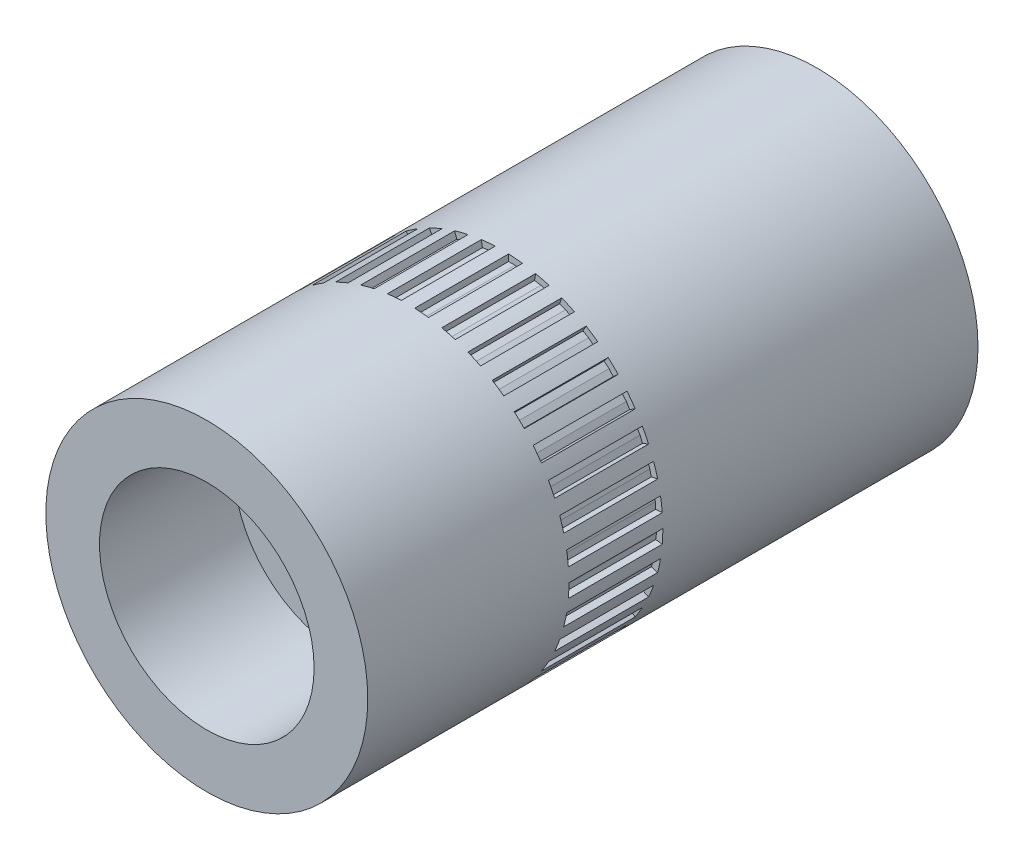
SolidWorks part; units mm, degrees
ref_plane "Ön Düzlem" through (0, 0, 0) normal (0, 0, 1) x (1, 0, 0)
ref_plane "Üst Düzlem" through (0, 0, 0) normal (0, 1, 0) x (1, 0, 0)
ref_plane "Sağ Düzlem" through (0, 0, 0) normal (1, 0, 0) x (0, 0, -1)
sketch "Çizim1" plane through (0, 0, 0) normal (0, 0, 1) x (1, 0, 0)
  circle A0 centre (0, 0) radius 9.1
  circle A1 centre (0, 0) radius 11
  circle A2 centre (0, 0) radius 12.559
  dimension "D1" = 18.2
  dimension "D2" = 22
extrude "Yükseklik-Ekstrüzyon1" add sketch "Çizim1" along normal blind 26.5 contours A1 A0
sketch "Çizim2" plane through (0, 0, 26.5) normal (0, 0, 1) x (1, 0, 0)
  circle A0 centre (0, 0) radius 12
  circle A1 centre (0, 0) radius 11
  circle A2 centre (0, 0) radius 11
  dimension "D2" = 24
  dimension "D1" = 0
extrude "Yükseklik-Ekstrüzyon2" add sketch "Çizim2" against normal blind 30.5
sketch "Çizim3" plane through (0, 0, 26.5) normal (0, 0, 1) x (1, 0, 0)
  line L0 (0, 12) -> (0, 11.629)
  line L1 (-0.5002, 12) -> (0.5002, 12)
  line L2 (0.5002, 12) -> (0.5002, 11.5)
  line L3 (-0.5002, 12) -> (-0.5002, 11.5)
  line L4 (0.5002, 11.5) -> (1.0002, 11.5)
  line L5 (-0.5002, 11.5) -> (-1.0002, 11.5)
  line L6 (1.4505, 11.4191) -> (0.9577, 11.5036)
  line L7 (1.535, 11.9119) -> (1.4505, 11.4191)
  line L8 (2.4365, 11.2501) -> (2.9293, 11.1656)
  line L9 (2.521, 11.7429) -> (2.4365, 11.2501)
  line L10 (1.535, 11.9119) -> (2.521, 11.7429)
  line L11 (3.3595, 11.0097) -> (2.8881, 11.1763)
  line L12 (3.5261, 11.4812) -> (3.3595, 11.0097)
  line L13 (4.3027, 10.6765) -> (4.7741, 10.5099)
  line L14 (4.4693, 11.1479) -> (4.3027, 10.6765)
  line L15 (3.5261, 11.4812) -> (4.4693, 11.1479)
  line L16 (5.1718, 10.2836) -> (4.7353, 10.5274)
  line L17 (5.4157, 10.7201) -> (5.1718, 10.2836)
  line L18 (6.0451, 9.7957) -> (6.4816, 9.5519)
  line L19 (6.289, 10.2322) -> (6.0451, 9.7957)
  line L20 (5.4157, 10.7201) -> (6.289, 10.2322)
  line L21 (6.8354, 9.2616) -> (6.4464, 9.5757)
  line L22 (7.1495, 9.6506) -> (6.8354, 9.2616)
  line L23 (7.6137, 8.6332) -> (8.0027, 8.3191)
  line L24 (7.9278, 9.0222) -> (7.6137, 8.6332)
  line L25 (7.1495, 9.6506) -> (7.9278, 9.0222)
  line L26 (8.3023, 7.9732) -> (7.972, 8.3486)
  line L27 (8.6776, 8.3036) -> (8.3023, 7.9732)
  line L28 (8.9632, 7.2223) -> (9.2935, 6.847)
  line L29 (9.3385, 7.5526) -> (8.9632, 7.2223)
  line L30 (8.6776, 8.3036) -> (9.3385, 7.5526)
  line L31 (9.5303, 6.4554) -> (9.2682, 6.8812)
  line L32 (9.9561, 6.7176) -> (9.5303, 6.4554)
  line L33 (10.0548, 5.6036) -> (10.317, 5.1779)
  line L34 (10.4806, 5.8658) -> (10.0548, 5.6036)
  line L35 (9.9561, 6.7176) -> (10.4806, 5.8658)
  line L36 (10.4842, 4.7519) -> (10.2978, 5.2159)
  line L37 (10.9482, 4.9384) -> (10.4842, 4.7519)
  line L38 (10.8572, 3.8238) -> (11.0436, 3.3598)
  line L39 (11.3212, 4.0102) -> (10.8572, 3.8238)
  line L40 (10.9482, 4.9384) -> (11.3212, 4.0102)
  line L41 (11.1365, 2.9117) -> (11.0312, 3.4005)
  line L42 (11.6253, 3.0171) -> (11.1365, 2.9117)
  line L43 (11.3473, 1.9339) -> (11.4526, 1.4451)
  line L44 (11.836, 2.0392) -> (11.3473, 1.9339)
  line L45 (11.6253, 3.0171) -> (11.836, 2.0392)
  line L46 (11.4684, 0.9878) -> (11.4472, 1.4873)
  line L47 (11.968, 1.009) -> (11.4684, 0.9878)
  line L48 (11.5109, -0.0116) -> (11.5321, -0.5112)
  line L49 (12.0104, 0.0096) -> (11.5109, -0.0116)
  line L50 (11.968, 1.009) -> (12.0104, 0.0096)
  line L51 (11.4704, -0.9646) -> (11.5339, -0.4686)
  line L52 (11.9663, -1.0281) -> (11.4704, -0.9646)
  line L53 (11.3433, -1.9568) -> (11.2798, -2.4528)
  line L54 (11.8393, -2.0203) -> (11.3433, -1.9568)
  line L55 (11.9663, -1.0281) -> (11.8393, -2.0203)
  line L56 (11.1424, -2.8892) -> (11.2888, -2.4111)
  line L57 (11.6205, -3.0356) -> (11.1424, -2.8892)
  line L58 (10.8495, -3.8457) -> (10.703, -4.3238)
  line L59 (11.3275, -3.9921) -> (10.8495, -3.8457)
  line L60 (11.6205, -3.0356) -> (11.3275, -3.9921)
  line L61 (10.4938, -4.7307) -> (10.7189, -4.2843)
  line L62 (10.9403, -4.9558) -> (10.4938, -4.7307)
  line L63 (10.0435, -5.6239) -> (9.8184, -6.0704)
  line L64 (10.4899, -5.8491) -> (10.0435, -5.6239)
  line L65 (10.9403, -4.9558) -> (10.4899, -5.8491)
  line L66 (9.5434, -6.4362) -> (9.8407, -6.0342)
  line L67 (9.9454, -6.7335) -> (9.5434, -6.4362)
  line L68 (8.9486, -7.2404) -> (8.6512, -7.6424)
  line L69 (9.3506, -7.5377) -> (8.9486, -7.2404)
  line L70 (9.9454, -6.7335) -> (9.3506, -7.5377)
  line L71 (8.3184, -7.9564) -> (8.6794, -7.6104)
  line L72 (8.6644, -8.3174) -> (8.3184, -7.9564)
  line L73 (7.5962, -8.6486) -> (7.2352, -8.9945)
  line L74 (7.9422, -9.0096) -> (7.5962, -8.6486)
  line L75 (8.6644, -8.3174) -> (7.9422, -9.0096)
  line L76 (6.8541, -9.2478) -> (7.2684, -8.9678)
  line L77 (7.1341, -9.662) -> (6.8541, -9.2478)
  line L78 (6.0253, -9.8079) -> (5.6111, -10.0879)
  line L79 (6.3053, -10.2222) -> (6.0253, -9.8079)
  line L80 (7.1341, -9.662) -> (6.3053, -10.2222)
  line L81 (5.1926, -10.2731) -> (5.6482, -10.0672)
  line L82 (5.3986, -10.7287) -> (5.1926, -10.2731)
  line L83 (4.2811, -10.6851) -> (3.8255, -10.8911)
  line L84 (4.4871, -11.1408) -> (4.2811, -10.6851)
  line L85 (5.3986, -10.7287) -> (4.4871, -11.1408)
  line L86 (3.3818, -11.0029) -> (3.8656, -10.8769)
  line L87 (3.5078, -11.4868) -> (3.3818, -11.0029)
  line L88 (2.4137, -11.255) -> (1.9299, -11.3809)
  line L89 (2.5397, -11.7388) -> (2.4137, -11.255)
  line L90 (3.5078, -11.4868) -> (2.5397, -11.7388)
  line L91 (1.4736, -11.4162) -> (1.9718, -11.3738)
  line L92 (1.516, -11.9144) -> (1.4736, -11.4162)
  line L93 (0.4769, -11.501) -> (-0.0213, -11.5434)
  line L94 (0.5193, -11.9992) -> (0.4769, -11.501)
  line L95 (1.516, -11.9144) -> (0.5193, -11.9992)
  line L96 (-0.4769, -11.501) -> (0.0213, -11.5434)
  line L97 (-0.5193, -11.9992) -> (-0.4769, -11.501)
  line L98 (-1.4736, -11.4162) -> (-1.9718, -11.3738)
  line L99 (-1.516, -11.9144) -> (-1.4736, -11.4162)
  line L100 (-0.5193, -11.9992) -> (-1.516, -11.9144)
  line L101 (-2.4137, -11.255) -> (-1.9299, -11.3809)
  line L102 (-2.5397, -11.7388) -> (-2.4137, -11.255)
  line L103 (-3.3818, -11.0029) -> (-3.8656, -10.8769)
  line L104 (-3.5078, -11.4868) -> (-3.3818, -11.0029)
  line L105 (-2.5397, -11.7388) -> (-3.5078, -11.4868)
  line L106 (-4.2811, -10.6851) -> (-3.8255, -10.8911)
  line L107 (-4.4871, -11.1408) -> (-4.2811, -10.6851)
  line L108 (-5.1926, -10.2731) -> (-5.6482, -10.0672)
  line L109 (-5.3986, -10.7287) -> (-5.1926, -10.2731)
  line L110 (-4.4871, -11.1408) -> (-5.3986, -10.7287)
  line L111 (-6.0253, -9.8079) -> (-5.6111, -10.0879)
  line L112 (-6.3053, -10.2222) -> (-6.0253, -9.8079)
  line L113 (-6.8541, -9.2478) -> (-7.2684, -8.9678)
  line L114 (-7.1341, -9.662) -> (-6.8541, -9.2478)
  line L115 (-6.3053, -10.2222) -> (-7.1341, -9.662)
  line L116 (-7.5962, -8.6486) -> (-7.2352, -8.9945)
  line L117 (-7.9422, -9.0096) -> (-7.5962, -8.6486)
  line L118 (-8.3184, -7.9564) -> (-8.6794, -7.6104)
  line L119 (-8.6644, -8.3174) -> (-8.3184, -7.9564)
  line L120 (-7.9422, -9.0096) -> (-8.6644, -8.3174)
  line L121 (-8.9486, -7.2404) -> (-8.6512, -7.6424)
  line L122 (-9.3506, -7.5377) -> (-8.9486, -7.2404)
  line L123 (-9.5434, -6.4362) -> (-9.8407, -6.0342)
  line L124 (-9.9454, -6.7335) -> (-9.5434, -6.4362)
  line L125 (-9.3506, -7.5377) -> (-9.9454, -6.7335)
  line L126 (-10.0435, -5.6239) -> (-9.8184, -6.0704)
  line L127 (-10.4899, -5.8491) -> (-10.0435, -5.6239)
  line L128 (-10.4938, -4.7307) -> (-10.7189, -4.2843)
  line L129 (-10.9403, -4.9558) -> (-10.4938, -4.7307)
  line L130 (-10.4899, -5.8491) -> (-10.9403, -4.9558)
  line L131 (-10.8495, -3.8457) -> (-10.703, -4.3238)
  line L132 (-11.3275, -3.9921) -> (-10.8495, -3.8457)
  line L133 (-11.1424, -2.8892) -> (-11.2888, -2.4111)
  line L134 (-11.6205, -3.0356) -> (-11.1424, -2.8892)
  line L135 (-11.3275, -3.9921) -> (-11.6205, -3.0356)
  line L136 (-11.3433, -1.9568) -> (-11.2798, -2.4528)
  line L137 (-11.8393, -2.0203) -> (-11.3433, -1.9568)
  line L138 (-11.4704, -0.9646) -> (-11.5339, -0.4686)
  line L139 (-11.9663, -1.0281) -> (-11.4704, -0.9646)
  line L140 (-11.8393, -2.0203) -> (-11.9663, -1.0281)
  line L141 (-11.5109, -0.0116) -> (-11.5321, -0.5112)
  line L142 (-12.0104, 0.0096) -> (-11.5109, -0.0116)
  line L143 (-11.4684, 0.9878) -> (-11.4472, 1.4873)
  line L144 (-11.968, 1.009) -> (-11.4684, 0.9878)
  line L145 (-12.0104, 0.0096) -> (-11.968, 1.009)
  line L146 (-11.3473, 1.9339) -> (-11.4526, 1.4451)
  line L147 (-11.836, 2.0392) -> (-11.3473, 1.9339)
  line L148 (-11.1365, 2.9117) -> (-11.0312, 3.4005)
  line L149 (-11.6253, 3.0171) -> (-11.1365, 2.9117)
  line L150 (-11.836, 2.0392) -> (-11.6253, 3.0171)
  line L151 (-10.8572, 3.8238) -> (-11.0436, 3.3598)
  line L152 (-11.3212, 4.0102) -> (-10.8572, 3.8238)
  line L153 (-10.4842, 4.7519) -> (-10.2978, 5.2159)
  line L154 (-10.9482, 4.9384) -> (-10.4842, 4.7519)
  line L155 (-11.3212, 4.0102) -> (-10.9482, 4.9384)
  line L156 (-10.0548, 5.6036) -> (-10.317, 5.1779)
  line L157 (-10.4806, 5.8658) -> (-10.0548, 5.6036)
  line L158 (-9.5303, 6.4554) -> (-9.2682, 6.8812)
  line L159 (-9.9561, 6.7176) -> (-9.5303, 6.4554)
  line L160 (-10.4806, 5.8658) -> (-9.9561, 6.7176)
  line L161 (-8.9632, 7.2223) -> (-9.2935, 6.847)
  line L162 (-9.3385, 7.5526) -> (-8.9632, 7.2223)
  line L163 (-8.3023, 7.9732) -> (-7.972, 8.3486)
  line L164 (-8.6776, 8.3036) -> (-8.3023, 7.9732)
  line L165 (-9.3385, 7.5526) -> (-8.6776, 8.3036)
  line L166 (-7.6137, 8.6332) -> (-8.0027, 8.3191)
  line L167 (-7.9278, 9.0222) -> (-7.6137, 8.6332)
  line L168 (-6.8354, 9.2616) -> (-6.4464, 9.5757)
  line L169 (-7.1495, 9.6506) -> (-6.8354, 9.2616)
  line L170 (-7.9278, 9.0222) -> (-7.1495, 9.6506)
  line L171 (-6.0451, 9.7957) -> (-6.4816, 9.5519)
  line L172 (-6.289, 10.2322) -> (-6.0451, 9.7957)
  line L173 (-5.1718, 10.2836) -> (-4.7353, 10.5274)
  line L174 (-5.4157, 10.7201) -> (-5.1718, 10.2836)
  line L175 (-6.289, 10.2322) -> (-5.4157, 10.7201)
  line L176 (-4.3027, 10.6765) -> (-4.7741, 10.5099)
  line L177 (-4.4693, 11.1479) -> (-4.3027, 10.6765)
  line L178 (-3.3595, 11.0097) -> (-2.8881, 11.1763)
  line L179 (-3.5261, 11.4812) -> (-3.3595, 11.0097)
  line L180 (-4.4693, 11.1479) -> (-3.5261, 11.4812)
  line L181 (-2.4365, 11.2501) -> (-2.9293, 11.1656)
  line L182 (-2.521, 11.7429) -> (-2.4365, 11.2501)
  line L183 (-1.4505, 11.4191) -> (-0.9577, 11.5036)
  line L184 (-1.535, 11.9119) -> (-1.4505, 11.4191)
  line L185 (-2.521, 11.7429) -> (-1.535, 11.9119)
  circle A1 centre (0, 0) radius 12
  circle A2 centre (0, 0) radius 12
  dimension "D2" = 0.5002
  dimension "D3" = 0.5
  dimension "D4" = 0.5
  dimension "D1" = 0
  dimension "D5" = 37
extrude "Kes-Ekstrüzyon1" cut sketch "Çizim3" against normal blind 7
sketch "Çizim4" plane through (0, 0, 26.5) normal (0, 0, 1) x (1, 0, 0)
  line L148 (-6.2839, 10.2231) -> (-6.0451, 9.7957)
  line L149 (-6.0451, 9.7957) -> (-6.463, 9.5623)
  line L150 (-6.463, 9.5623) -> (-6.8354, 9.2616)
  line L151 (-6.8354, 9.2616) -> (-7.1429, 9.6425)
  line L152 (-7.9212, 9.0141) -> (-7.6137, 8.6332)
  line L153 (-7.6137, 8.6332) -> (-7.9861, 8.3325)
  line L154 (-7.9861, 8.3325) -> (-8.3023, 7.9732)
  line L155 (-8.3023, 7.9732) -> (-8.6698, 8.2967)
  line L156 (-9.3307, 7.5458) -> (-8.9632, 7.2223)
  line L157 (-8.9632, 7.2223) -> (-9.2794, 6.863)
  line L158 (-9.2794, 6.863) -> (-9.5303, 6.4554)
  line L159 (-9.5303, 6.4554) -> (-9.9472, 6.7121)
  line L160 (-10.4717, 5.8603) -> (-10.0548, 5.6036)
  line L161 (-10.0548, 5.6036) -> (-10.3058, 5.1961)
  line L162 (-10.3058, 5.1961) -> (-10.4842, 4.7519)
  line L163 (-10.4842, 4.7519) -> (-10.9385, 4.9345)
  line L164 (-11.3115, 4.0063) -> (-10.8572, 3.8238)
  line L165 (-10.8572, 3.8238) -> (-11.0357, 3.3796)
  line L166 (-11.0357, 3.3796) -> (-11.1365, 2.9117)
  line L167 (-11.1365, 2.9117) -> (-11.6151, 3.0149)
  line L168 (-11.8258, 2.037) -> (-11.3473, 1.9339)
  line L169 (-11.3473, 1.9339) -> (-11.4481, 1.466)
  line L170 (-11.4481, 1.466) -> (-11.4684, 0.9878)
  line L171 (-11.4684, 0.9878) -> (-11.9575, 1.0086)
  line L172 (-12, 0.0091) -> (-11.5109, -0.0116)
  line L173 (-11.5109, -0.0116) -> (-11.5312, -0.4898)
  line L174 (-11.5312, -0.4898) -> (-11.4704, -0.9646)
  line L175 (-11.4704, -0.9646) -> (-11.956, -1.0268)
  line L176 (-11.8289, -2.019) -> (-11.3433, -1.9568)
  line L177 (-11.3433, -1.9568) -> (-11.2825, -2.4316)
  line L178 (-11.2825, -2.4316) -> (-11.1424, -2.8892)
  line L179 (-11.1424, -2.8892) -> (-11.6105, -3.0326)
  line L180 (-11.3176, -3.9891) -> (-10.8495, -3.8457)
  line L181 (-10.8495, -3.8457) -> (-10.7093, -4.3034)
  line L182 (-10.7093, -4.3034) -> (-10.4938, -4.7307)
  line L183 (-10.4938, -4.7307) -> (-10.931, -4.9511)
  line L184 (-10.4806, -5.8444) -> (-10.0435, -5.6239)
  line L185 (-10.0435, -5.6239) -> (-9.828, -6.0513)
  line L186 (-9.828, -6.0513) -> (-9.5434, -6.4362)
  line L187 (-9.5434, -6.4362) -> (-9.937, -6.7273)
  line L188 (-9.3422, -7.5315) -> (-8.9486, -7.2404)
  line L189 (-8.9486, -7.2404) -> (-8.6639, -7.6252)
  line L190 (-8.6639, -7.6252) -> (-8.3184, -7.9564)
  line L191 (-8.3184, -7.9564) -> (-8.6571, -8.3099)
  line L192 (-7.935, -9.002) -> (-7.5962, -8.6486)
  line L193 (-7.5962, -8.6486) -> (-7.2507, -8.9798)
  line L194 (-7.2507, -8.9798) -> (-6.8541, -9.2478)
  line L195 (-6.8541, -9.2478) -> (-7.1282, -9.6534)
  line L196 (-6.2995, -10.2136) -> (-6.0253, -9.8079)
  line L197 (-6.0253, -9.8079) -> (-5.6288, -10.076)
  line L198 (-5.6288, -10.076) -> (-5.1926, -10.2731)
  line L199 (-5.1926, -10.2731) -> (-5.3943, -10.7192)
  line L200 (-4.4828, -11.1313) -> (-4.2811, -10.6851)
  line L201 (-4.2811, -10.6851) -> (-3.845, -10.8823)
  line L202 (-3.845, -10.8823) -> (-3.3818, -11.0029)
  line L203 (-3.3818, -11.0029) -> (-3.5051, -11.4767)
  line L204 (-2.5371, -11.7287) -> (-2.4137, -11.255)
  line L205 (-2.4137, -11.255) -> (-1.9505, -11.3756)
  line L206 (-1.9505, -11.3756) -> (-1.4736, -11.4162)
  line L207 (-1.4736, -11.4162) -> (-1.5151, -11.904)
  line L208 (-0.5184, -11.9888) -> (-0.4769, -11.501)
  line L209 (-0.4769, -11.501) -> (0, -11.5416)
  line L210 (0, -11.5416) -> (0.4769, -11.501)
  line L211 (0.4769, -11.501) -> (0.5184, -11.9888)
  line L212 (1.5151, -11.904) -> (1.4736, -11.4162)
  line L213 (1.4736, -11.4162) -> (1.9505, -11.3756)
  line L214 (1.9505, -11.3756) -> (2.4137, -11.255)
  line L215 (2.4137, -11.255) -> (2.5371, -11.7287)
  line L216 (3.5051, -11.4767) -> (3.3818, -11.0029)
  line L217 (3.3818, -11.0029) -> (3.845, -10.8823)
  line L218 (3.845, -10.8823) -> (4.2811, -10.6851)
  line L219 (4.2811, -10.6851) -> (4.4828, -11.1313)
  line L220 (5.3943, -10.7192) -> (5.1926, -10.2731)
  line L221 (5.1926, -10.2731) -> (5.6288, -10.076)
  line L222 (5.6288, -10.076) -> (6.0253, -9.8079)
  line L223 (6.0253, -9.8079) -> (6.2995, -10.2136)
  line L224 (7.1282, -9.6534) -> (6.8541, -9.2478)
  line L225 (6.8541, -9.2478) -> (7.2507, -8.9798)
  line L226 (7.2507, -8.9798) -> (7.5962, -8.6486)
  line L227 (7.5962, -8.6486) -> (7.935, -9.002)
  line L228 (8.6571, -8.3099) -> (8.3184, -7.9564)
  line L229 (8.3184, -7.9564) -> (8.6639, -7.6252)
  line L230 (8.6639, -7.6252) -> (8.9486, -7.2404)
  line L231 (8.9486, -7.2404) -> (9.3422, -7.5315)
  line L232 (9.937, -6.7273) -> (9.5434, -6.4362)
  line L233 (9.5434, -6.4362) -> (9.828, -6.0513)
  line L234 (9.828, -6.0513) -> (10.0435, -5.6239)
  line L235 (10.0435, -5.6239) -> (10.4806, -5.8444)
  line L236 (10.931, -4.9511) -> (10.4938, -4.7307)
  line L237 (10.4938, -4.7307) -> (10.7093, -4.3034)
  line L238 (10.7093, -4.3034) -> (10.8495, -3.8457)
  line L239 (10.8495, -3.8457) -> (11.3176, -3.9891)
  line L240 (11.6105, -3.0326) -> (11.1424, -2.8892)
  line L241 (11.1424, -2.8892) -> (11.2825, -2.4316)
  line L242 (11.2825, -2.4316) -> (11.3433, -1.9568)
  line L243 (11.3433, -1.9568) -> (11.8289, -2.019)
  line L244 (11.956, -1.0268) -> (11.4704, -0.9646)
  line L245 (11.4704, -0.9646) -> (11.5312, -0.4898)
  line L246 (11.5312, -0.4898) -> (11.5109, -0.0116)
  line L247 (11.5109, -0.0116) -> (12, 0.0091)
  line L248 (11.9575, 1.0086) -> (11.4684, 0.9878)
  line L249 (11.4684, 0.9878) -> (11.4481, 1.466)
  line L250 (11.4481, 1.466) -> (11.3473, 1.9339)
  line L251 (11.3473, 1.9339) -> (11.8258, 2.037)
  line L252 (11.6151, 3.0149) -> (11.1365, 2.9117)
  line L253 (11.1365, 2.9117) -> (11.0357, 3.3796)
  line L254 (11.0357, 3.3796) -> (10.8572, 3.8238)
  line L255 (10.8572, 3.8238) -> (11.3115, 4.0063)
  line L256 (10.9385, 4.9345) -> (10.4842, 4.7519)
  line L257 (10.4842, 4.7519) -> (10.3058, 5.1961)
  line L258 (10.3058, 5.1961) -> (10.0548, 5.6036)
  line L259 (10.0548, 5.6036) -> (10.4717, 5.8603)
  line L260 (9.9472, 6.7121) -> (9.5303, 6.4554)
  line L261 (9.5303, 6.4554) -> (9.2794, 6.863)
  line L262 (9.2794, 6.863) -> (8.9632, 7.2223)
  line L263 (8.9632, 7.2223) -> (9.3307, 7.5458)
  line L264 (8.6698, 8.2967) -> (8.3023, 7.9732)
  line L265 (8.3023, 7.9732) -> (7.9861, 8.3325)
  line L266 (7.9861, 8.3325) -> (7.6137, 8.6332)
  line L267 (7.6137, 8.6332) -> (7.9212, 9.0141)
  line L268 (7.1429, 9.6425) -> (6.8354, 9.2616)
  line L269 (6.8354, 9.2616) -> (6.463, 9.5623)
  line L270 (6.463, 9.5623) -> (6.0451, 9.7957)
  line L271 (6.0451, 9.7957) -> (6.2839, 10.2231)
  line L272 (5.4106, 10.711) -> (5.1718, 10.2836)
  line L273 (5.1718, 10.2836) -> (4.754, 10.517)
  line L274 (4.754, 10.517) -> (4.3027, 10.6765)
  line L275 (4.3027, 10.6765) -> (4.4658, 11.1381)
  line L276 (3.5226, 11.4713) -> (3.3595, 11.0097)
  line L277 (3.3595, 11.0097) -> (2.9082, 11.1692)
  line L278 (2.9082, 11.1692) -> (2.4365, 11.2501)
  line L279 (2.4365, 11.2501) -> (2.5192, 11.7326)
  line L280 (1.5333, 11.9016) -> (1.4505, 11.4191)
  line L281 (1.4505, 11.4191) -> (0.9788, 11.5)
  line L282 (0.9788, 11.5) -> (0.5002, 11.5)
  line L283 (0.5002, 11.5) -> (0.5002, 11.9896)
  line L284 (-0.5002, 11.9896) -> (-0.5002, 11.5)
  line L285 (-0.5002, 11.5) -> (-0.9788, 11.5)
  line L286 (-0.9788, 11.5) -> (-1.4505, 11.4191)
  line L287 (-1.4505, 11.4191) -> (-1.5333, 11.9016)
  line L288 (-2.5192, 11.7326) -> (-2.4365, 11.2501)
  line L289 (-2.4365, 11.2501) -> (-2.9082, 11.1692)
  line L290 (-2.9082, 11.1692) -> (-3.3595, 11.0097)
  line L291 (-3.3595, 11.0097) -> (-3.5226, 11.4713)
  line L292 (-4.4658, 11.1381) -> (-4.3027, 10.6765)
  line L293 (-4.3027, 10.6765) -> (-4.754, 10.517)
  line L294 (-4.754, 10.517) -> (-5.1718, 10.2836)
  line L295 (-5.1718, 10.2836) -> (-5.4106, 10.711)
  circle A0 centre (0, 0) radius 12
  arc A37 (-5.4106, 10.711) -> (-6.2839, 10.2231) centre (0, 0) ccw
  arc A38 (-7.1429, 9.6425) -> (-7.9212, 9.0141) centre (0, 0) ccw
  arc A39 (-8.6698, 8.2967) -> (-9.3307, 7.5458) centre (0, 0) ccw
  arc A40 (-9.9472, 6.7121) -> (-10.4717, 5.8603) centre (0, 0) ccw
  arc A41 (-10.9385, 4.9345) -> (-11.3115, 4.0063) centre (0, 0) ccw
  arc A42 (-11.6151, 3.0149) -> (-11.8258, 2.037) centre (0, 0) ccw
  arc A43 (-11.9575, 1.0086) -> (-12, 0.0091) centre (0, 0) ccw
  arc A44 (-11.956, -1.0268) -> (-11.8289, -2.019) centre (0, 0) ccw
  arc A45 (-11.6105, -3.0326) -> (-11.3176, -3.9891) centre (0, 0) ccw
  arc A46 (-10.931, -4.9511) -> (-10.4806, -5.8444) centre (0, 0) ccw
  arc A47 (-9.937, -6.7273) -> (-9.3422, -7.5315) centre (0, 0) ccw
  arc A48 (-8.6571, -8.3099) -> (-7.935, -9.002) centre (0, 0) ccw
  arc A49 (-7.1282, -9.6534) -> (-6.2995, -10.2136) centre (0, 0) ccw
  arc A50 (-5.3943, -10.7192) -> (-4.4828, -11.1313) centre (0, 0) ccw
  arc A51 (-3.5051, -11.4767) -> (-2.5371, -11.7287) centre (0, 0) ccw
  arc A52 (-1.5151, -11.904) -> (-0.5184, -11.9888) centre (0, 0) ccw
  arc A53 (0.5184, -11.9888) -> (1.5151, -11.904) centre (0, 0) ccw
  arc A54 (2.5371, -11.7287) -> (3.5051, -11.4767) centre (0, 0) ccw
  arc A55 (4.4828, -11.1313) -> (5.3943, -10.7192) centre (0, 0) ccw
  arc A56 (6.2995, -10.2136) -> (7.1282, -9.6534) centre (0, 0) ccw
  arc A57 (7.935, -9.002) -> (8.6571, -8.3099) centre (0, 0) ccw
  arc A58 (9.3422, -7.5315) -> (9.937, -6.7273) centre (0, 0) ccw
  arc A59 (10.4806, -5.8444) -> (10.931, -4.9511) centre (0, 0) ccw
  arc A60 (11.3176, -3.9891) -> (11.6105, -3.0326) centre (0, 0) ccw
  arc A61 (11.8289, -2.019) -> (11.956, -1.0268) centre (0, 0) ccw
  arc A62 (12, 0.0091) -> (11.9575, 1.0086) centre (0, 0) ccw
  arc A63 (11.8258, 2.037) -> (11.6151, 3.0149) centre (0, 0) ccw
  arc A64 (11.3115, 4.0063) -> (10.9385, 4.9345) centre (0, 0) ccw
  arc A65 (10.4717, 5.8603) -> (9.9472, 6.7121) centre (0, 0) ccw
  arc A66 (9.3307, 7.5458) -> (8.6698, 8.2967) centre (0, 0) ccw
  arc A67 (7.9212, 9.0141) -> (7.1429, 9.6425) centre (0, 0) ccw
  arc A68 (6.2839, 10.2231) -> (5.4106, 10.711) centre (0, 0) ccw
  arc A69 (4.4658, 11.1381) -> (3.5226, 11.4713) centre (0, 0) ccw
  arc A70 (2.5192, 11.7326) -> (1.5333, 11.9016) centre (0, 0) ccw
  arc A71 (0.5002, 11.9896) -> (-0.5002, 11.9896) centre (0, 0) ccw
  arc A72 (-1.5333, 11.9016) -> (-2.5192, 11.7326) centre (0, 0) ccw
  arc A73 (-3.5226, 11.4713) -> (-4.4658, 11.1381) centre (0, 0) ccw
  arc A74 (-5.4106, 10.711) -> (-6.2839, 10.2231) centre (0, 0) ccw
  arc A75 (-7.1429, 9.6425) -> (-7.9212, 9.0141) centre (0, 0) ccw
  arc A76 (-8.6698, 8.2967) -> (-9.3307, 7.5458) centre (0, 0) ccw
  arc A77 (-9.9472, 6.7121) -> (-10.4717, 5.8603) centre (0, 0) ccw
  arc A78 (-10.9385, 4.9345) -> (-11.3115, 4.0063) centre (0, 0) ccw
  arc A79 (-11.6151, 3.0149) -> (-11.8258, 2.037) centre (0, 0) ccw
  arc A80 (-11.9575, 1.0086) -> (-12, 0.0091) centre (0, 0) ccw
  arc A81 (-11.956, -1.0268) -> (-11.8289, -2.019) centre (0, 0) ccw
  arc A82 (-11.6105, -3.0326) -> (-11.3176, -3.9891) centre (0, 0) ccw
  arc A83 (-10.931, -4.9511) -> (-10.4806, -5.8444) centre (0, 0) ccw
  arc A84 (-9.937, -6.7273) -> (-9.3422, -7.5315) centre (0, 0) ccw
  arc A85 (-8.6571, -8.3099) -> (-7.935, -9.002) centre (0, 0) ccw
  arc A86 (-7.1282, -9.6534) -> (-6.2995, -10.2136) centre (0, 0) ccw
  arc A87 (-5.3943, -10.7192) -> (-4.4828, -11.1313) centre (0, 0) ccw
  arc A88 (-3.5051, -11.4767) -> (-2.5371, -11.7287) centre (0, 0) ccw
  arc A89 (-1.5151, -11.904) -> (-0.5184, -11.9888) centre (0, 0) ccw
  arc A90 (0.5184, -11.9888) -> (1.5151, -11.904) centre (0, 0) ccw
  arc A91 (2.5371, -11.7287) -> (3.5051, -11.4767) centre (0, 0) ccw
  arc A92 (4.4828, -11.1313) -> (5.3943, -10.7192) centre (0, 0) ccw
  arc A93 (6.2995, -10.2136) -> (7.1282, -9.6534) centre (0, 0) ccw
  arc A94 (7.935, -9.002) -> (8.6571, -8.3099) centre (0, 0) ccw
  arc A95 (9.3422, -7.5315) -> (9.937, -6.7273) centre (0, 0) ccw
  arc A96 (10.4806, -5.8444) -> (10.931, -4.9511) centre (0, 0) ccw
  arc A97 (11.3176, -3.9891) -> (11.6105, -3.0326) centre (0, 0) ccw
  arc A98 (11.8289, -2.019) -> (11.956, -1.0268) centre (0, 0) ccw
  arc A99 (12, 0.0091) -> (11.9575, 1.0086) centre (0, 0) ccw
  arc A100 (11.8258, 2.037) -> (11.6151, 3.0149) centre (0, 0) ccw
  arc A101 (11.3115, 4.0063) -> (10.9385, 4.9345) centre (0, 0) ccw
  arc A102 (10.4717, 5.8603) -> (9.9472, 6.7121) centre (0, 0) ccw
  arc A103 (9.3307, 7.5458) -> (8.6698, 8.2967) centre (0, 0) ccw
  arc A104 (7.9212, 9.0141) -> (7.1429, 9.6425) centre (0, 0) ccw
  arc A105 (6.2839, 10.2231) -> (5.4106, 10.711) centre (0, 0) ccw
  arc A106 (4.4658, 11.1381) -> (3.5226, 11.4713) centre (0, 0) ccw
  arc A107 (2.5192, 11.7326) -> (1.5333, 11.9016) centre (0, 0) ccw
  arc A108 (0.5002, 11.9896) -> (-0.5002, 11.9896) centre (0, 0) ccw
  arc A109 (-1.5333, 11.9016) -> (-2.5192, 11.7326) centre (0, 0) ccw
  arc A110 (-3.5226, 11.4713) -> (-4.4658, 11.1381) centre (0, 0) ccw
  dimension "D1" = 0
extrude "Yükseklik-Ekstrüzyon3" add sketch "Çizim4" along normal blind 5 contours A0
sketch "Çizim5" plane through (0, 0, 31.5) normal (0, 0, 1) x (1, 0, 0)
  circle A0 centre (0, 0) radius 8
  circle A1 centre (0, 0) radius 12
  circle A2 centre (0, 0) radius 12
  dimension "D2" = 16
  dimension "D1" = 0
extrude "Yükseklik-Ekstrüzyon4" add sketch "Çizim5" along normal blind 10
